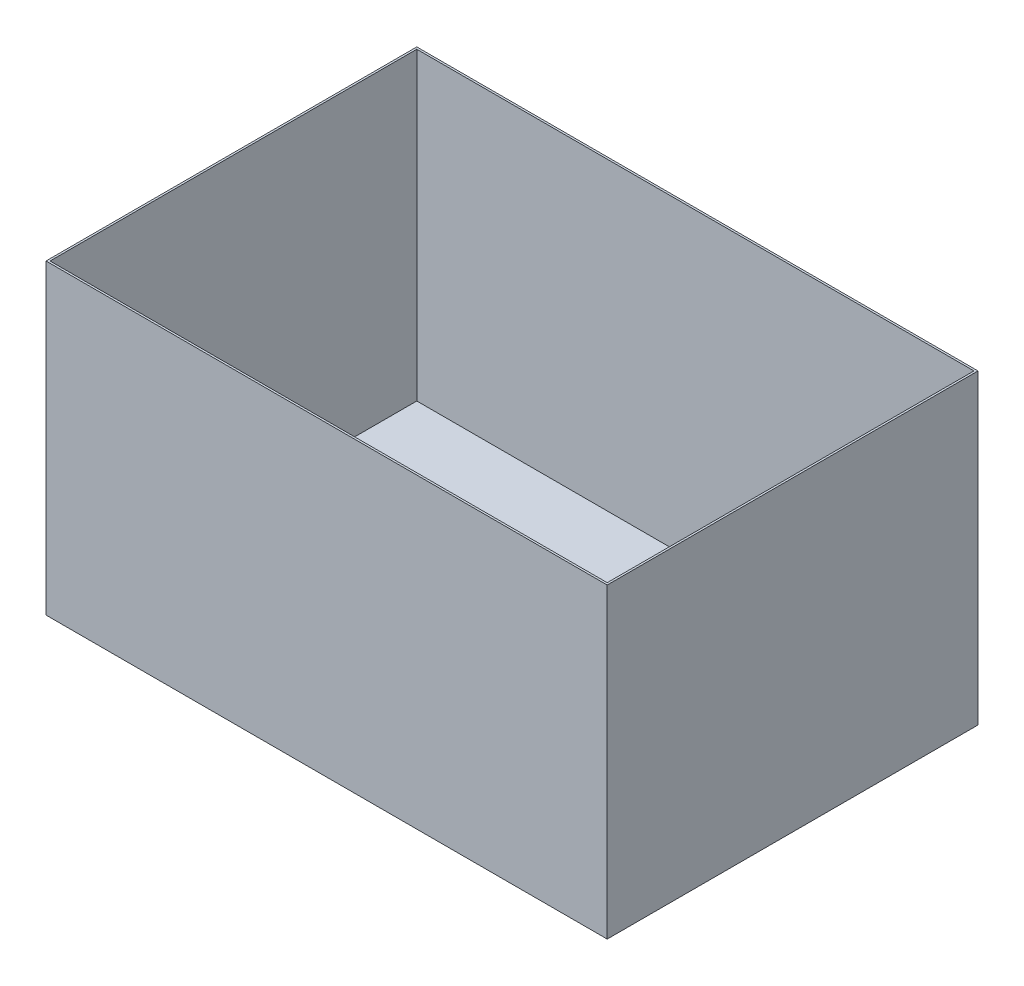
SolidWorks part; units mm, degrees
ref_plane "Front Plane" through (0, 0, 0) normal (0, 0, 1) x (1, 0, 0)
ref_plane "Top Plane" through (0, 0, 0) normal (0, 1, 0) x (1, 0, 0)
ref_plane "Right Plane" through (0, 0, 0) normal (1, 0, 0) x (0, 0, -1)
sketch "Sketch1" plane through (0, 0, 0) normal (0, 1, 0) x (1, 0, 0)
  line L1 (-355.6, -234.95) -> (355.6, -234.95)
  line L2 (-355.6, -234.95) -> (-355.6, 234.95)
  line L3 (-355.6, 234.95) -> (355.6, 234.95)
  line L4 (355.6, -234.95) -> (355.6, 234.95)
  line L5 (-355.6, -234.95) -> (355.6, 234.95) construction
  line L6 (-355.6, 234.95) -> (355.6, -234.95) construction
  point P0 (0, 0)
  dimension "D1" = 711.2
  dimension "D2" = 469.9
extrude "Boss-Extrude1" add sketch "Sketch1" along normal blind 388.62 contours L2 L3 L4 L1
shell "Shell1" thickness 2.54
